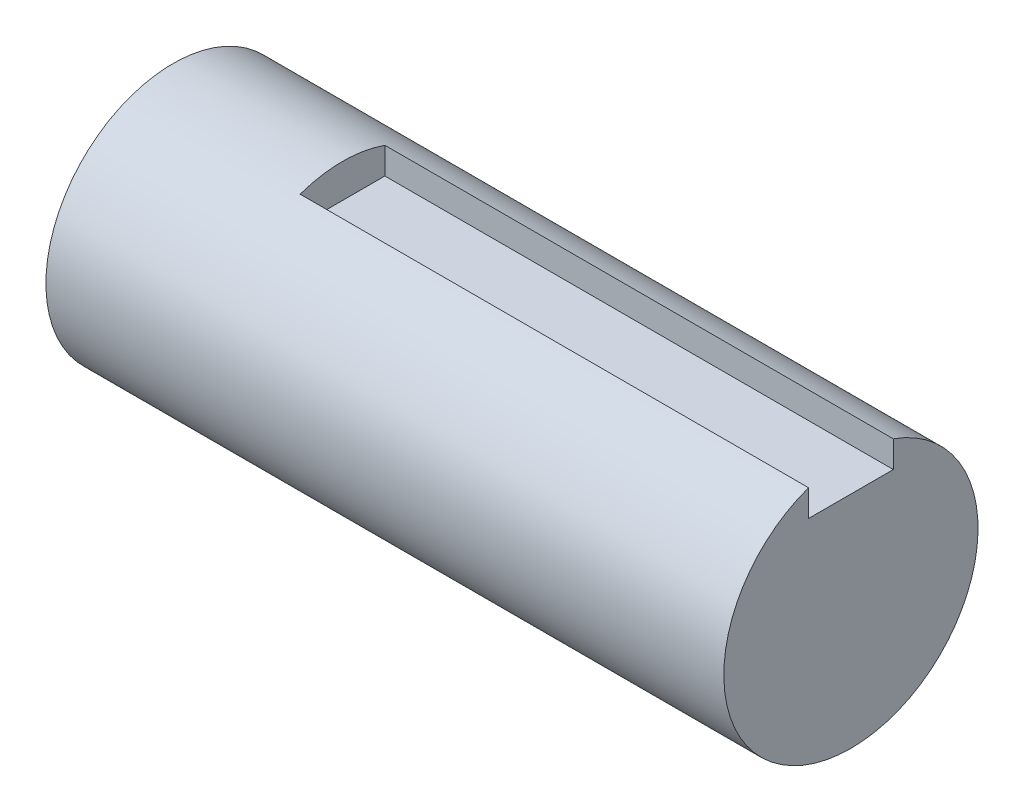
SolidWorks part; units mm, degrees
material "ABS"
ref_plane "Front Plane" through (0, 0, 0) normal (0, 0, 1) x (1, 0, 0)
ref_plane "Top Plane" through (0, 0, 0) normal (0, 1, 0) x (1, 0, 0)
ref_plane "Right Plane" through (0, 0, 0) normal (1, 0, 0) x (0, 0, -1)
sketch "Sketch1" plane through (0, 0, 0) normal (1, 0, 0) x (0, 0, -1)
  circle A0 centre (0, 0) radius 15
  dimension "D1" = 30
extrude "Boss-Extrude1" add sketch "Sketch1" along normal blind 80
sketch "Sketch2" plane through (80, 0, 0) normal (1, 0, 0) x (0, 0, -1)
  line L0 (0, 0) -> (0, 11)
  line L1 (-5, 15) -> (5, 15)
  line L2 (-5, 15) -> (-5, 11)
  line L3 (-5, 11) -> (5, 11)
  line L4 (5, 15) -> (5, 11)
  circle A0 centre (0, 0) radius 15 construction
  point P7 (0, 0)
  point P8 (0, 0)
  circle M4 centre (0, 0) radius 15
  dimension "D1" = 4
  dimension "D2" = 10
extrude "Cut-Extrude2" cut sketch "Sketch2" against normal blind 60 contours L4 L2 L3 M4
